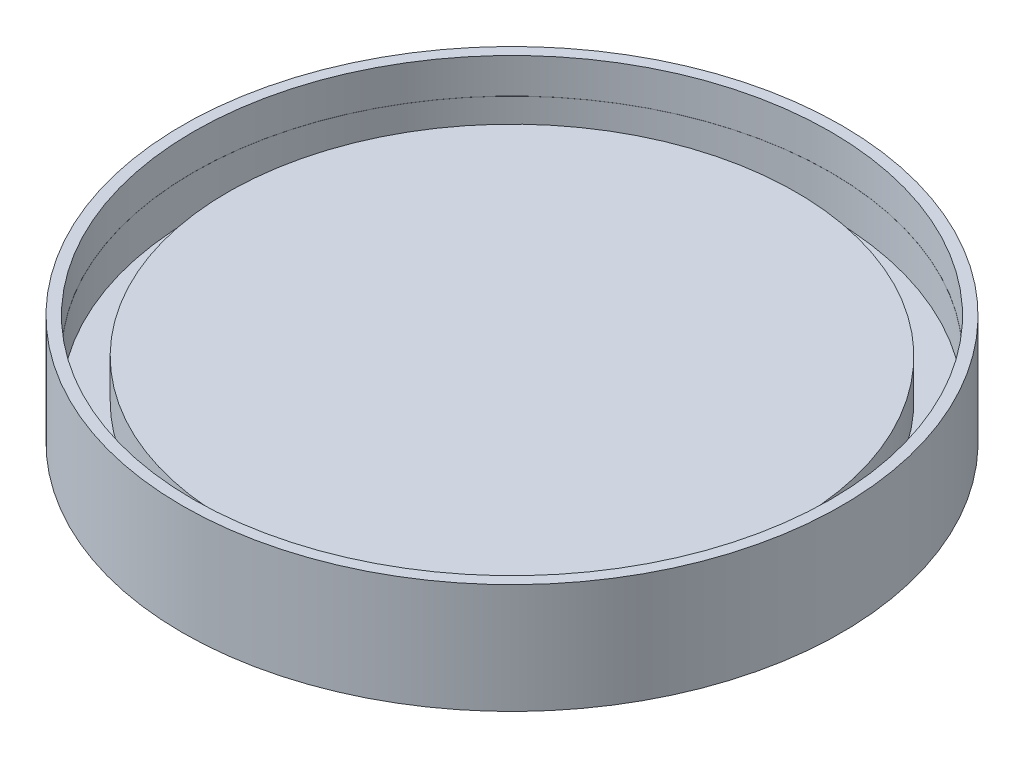
SolidWorks part; units mm, degrees
ref_plane "Front Plane" through (0, 0, 0) normal (0, 0, 1) x (1, 0, 0)
ref_plane "Top Plane" through (0, 0, 0) normal (0, 1, 0) x (1, 0, 0)
ref_plane "Right Plane" through (0, 0, 0) normal (1, 0, 0) x (0, 0, -1)
sketch "Sketch1" plane through (0, 0, 0) normal (0, 1, 0) x (1, 0, 0)
  circle A0 centre (0, 0) radius 45
  dimension "D1" = 90
extrude "Boss-Extrude1" add sketch "Sketch1" along normal blind 15
sketch "Sketch2" plane through (0, 15, 0) normal (0, 1, 0) x (1, 0, 0)
  circle A0 centre (0, 0) radius 43.5
  dimension "D1" = 87
extrude "Cut-Extrude1" cut sketch "Sketch2" against normal blind 4.8
sketch "Sketch3" plane through (0, 10.2, 0) normal (0, 1, 0) x (1, 0, 0)
  circle A0 centre (0, 0) radius 43.4879
  circle A1 centre (0, 0) radius 38.8
  dimension "D2" = 77.6
extrude "Cut-Extrude2" cut sketch "Sketch3" against normal blind 5.4
